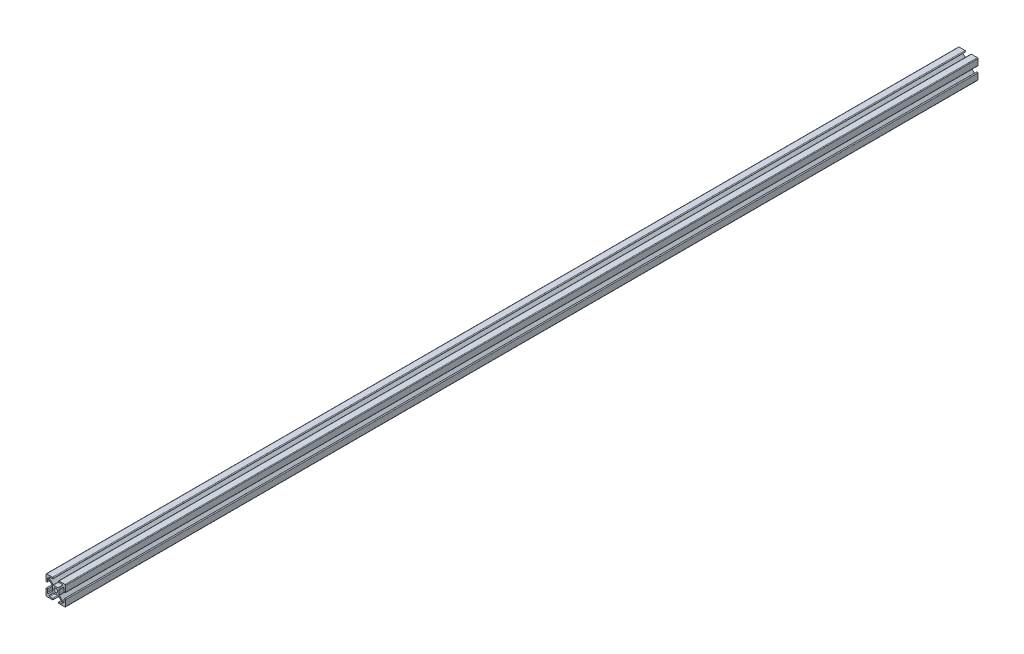
SolidWorks part; units mm, degrees
ref_plane "Alzado" through (0, 0, 0) normal (0, 0, 1) x (1, 0, 0)
ref_plane "Planta" through (0, 0, 0) normal (0, 1, 0) x (1, 0, 0)
ref_plane "Vista lateral" through (0, 0, 0) normal (1, 0, 0) x (0, 0, -1)
sketch "Croquis1" plane through (0, 0, 0) normal (0, 0, 1) x (1, 0, 0)
  line L1 (-14, 15) -> (14, 15)
  line L2 (-15, 14) -> (-15, -14)
  line L3 (-14, -15) -> (14, -15)
  line L4 (15, 14) -> (15, -14)
  line L5 (-15, 15) -> (15, -15) construction
  line L6 (-15, -15) -> (15, 15) construction
  arc A0 (-14, 15) -> (-15, 14) centre (-14, 14) ccw
  arc A1 (14, -15) -> (15, -14) centre (14, -14) ccw
  arc A2 (-14, -15) -> (-15, -14) centre (-14, -14) cw
  arc A3 (15, 14) -> (14, 15) centre (14, 14) ccw
  point P0 (0, 0)
  dimension "D3" = 1
  dimension "D4" = 1
  dimension "D1" = 30
  dimension "D2" = 30
extrude "Saliente-Extruir1" add sketch "Croquis1" against normal blind 1400
sketch "Croquis2" plane through (0, 0, 0) normal (0, 0, 1) x (1, 0, 0)
  circle A0 centre (0, 0) radius 3
  dimension "D1" = 6
sketch "Croquis3" plane through (0, 0, 0) normal (0, 0, 1) x (1, 0, 0)
  line L0 (-15, 0) -> (15, 0) construction
  line L1 (4.0787, -5.4929) -> (9.8787, -11.2929)
  line L2 (-11.2929, 9.8787) -> (-5.4929, 4.0787)
  line L3 (-9.8787, 11.2929) -> (-4.0787, 5.4929)
  line L4 (-13, 9.1716) -> (-13, 5)
  line L5 (-15, 14) -> (-15, -14) construction
  line L6 (-5.2, 3.3716) -> (-5.2, -3.3716)
  line L7 (-9.1716, 13) -> (-5, 13)
  line L8 (9.8787, 11.2929) -> (4.0787, 5.4929)
  line L9 (11.2929, 9.8787) -> (5.4929, 4.0787)
  line L10 (-3.3716, 5.2) -> (3.3716, 5.2)
  line L11 (14, 15) -> (-14, 15) construction
  line L12 (13, 9.1716) -> (13, 5)
  line L13 (5.2, 3.3716) -> (5.2, -3.3716)
  line L14 (15, -14) -> (15, 14) construction
  line L15 (-9.1716, -13) -> (-5, -13)
  line L16 (-3.3716, -5.2) -> (3.3716, -5.2)
  line L17 (-14, -15) -> (14, -15) construction
  line L18 (-5.4929, -4.0787) -> (-11.2929, -9.8787)
  line L19 (5.4929, -4.0787) -> (11.2929, -9.8787)
  line L20 (-4.0787, -5.4929) -> (-9.8787, -11.2929)
  line L21 (5, -13) -> (9.1716, -13)
  line L22 (-13, -5) -> (-13, -9.1716)
  line L23 (13, -5) -> (13, -9.1716)
  line L24 (0, 15) -> (0, -5.2) construction
  line L34 (5, 13) -> (9.1716, 13)
  arc A0 (9.8787, 11.2929) -> (9.1716, 13) centre (9.1716, 12) ccw
  arc A1 (-9.8787, 11.2929) -> (-9.1716, 13) centre (-9.1716, 12) cw
  arc A2 (9.8787, 11.2929) -> (9.1716, 13) centre (9.1716, 12) ccw
  arc A3 (13, 9.1716) -> (11.2929, 9.8787) centre (12, 9.1716) ccw
  arc A4 (11.2929, -9.8787) -> (13, -9.1716) centre (12, -9.1716) ccw
  arc A5 (9.1716, -13) -> (9.8787, -11.2929) centre (9.1716, -12) ccw
  arc A6 (-9.1716, -13) -> (-9.8787, -11.2929) centre (-9.1716, -12) cw
  arc A7 (-11.2929, -9.8787) -> (-13, -9.1716) centre (-12, -9.1716) cw
  arc A8 (-13, 9.1716) -> (-11.2929, 9.8787) centre (-12, 9.1716) cw
  arc A9 (-4.0787, -5.4929) -> (-3.3716, -5.2) centre (-3.3716, -6.2) cw
  arc A10 (3.3716, -5.2) -> (4.0787, -5.4929) centre (3.3716, -6.2) cw
  arc A11 (5.4929, -4.0787) -> (5.2, -3.3716) centre (6.2, -3.3716) cw
  arc A12 (5.2, 3.3716) -> (5.4929, 4.0787) centre (6.2, 3.3716) cw
  arc A13 (3.3716, 5.2) -> (4.0787, 5.4929) centre (3.3716, 6.2) ccw
  arc A14 (-3.3716, 5.2) -> (-4.0787, 5.4929) centre (-3.3716, 6.2) cw
  arc A15 (-5.4929, -4.0787) -> (-5.2, -3.3716) centre (-6.2, -3.3716) ccw
  arc A16 (-5.2, 3.3716) -> (-5.4929, 4.0787) centre (-6.2, 3.3716) ccw
  circle A17 centre (-14, -5) radius 1
  circle A18 centre (-14, 5) radius 1
  circle A19 centre (-5, -14) radius 1
  circle A20 centre (5, -14) radius 1
  circle A21 centre (14, 5) radius 1
  circle A22 centre (14, -5) radius 1
  circle A23 centre (-5, 14) radius 1
  circle A24 centre (5, 14) radius 1
  point P20 (-11.5858, -13)
  point P30 (-13, -11.5858)
  point P43 (-3.7858, -5.2)
  point P50 (3.7858, -5.2)
  point P53 (5.2, -3.7858)
  point P62 (-5.2, -3.7858)
  line M2 (-15, 14) -> (-15, -14)
  line M4 (-14, -15) -> (14, -15)
  line M6 (15, -14) -> (15, 14)
  line M8 (14, 15) -> (-14, 15)
  dimension "D6" = 9.8
  dimension "D7" = 2
  dimension "D12" = 2
  dimension "D19" = 1
  dimension "D2" = 1
  dimension "D3" = 1
  dimension "D4" = 1
  dimension "D16" = 1
  dimension "D5" = 2
  dimension "D8" = 9.8
  dimension "D9" = 2
  dimension "D10" = 9.8
  dimension "D11" = 9.8
  dimension "D15" = 1
  dimension "D20" = 1
  dimension "D23" = 1
  dimension "D24" = 1
  dimension "D27" = 1
  dimension "D28" = 1
extrude "Cortar-Extruir1" cut sketch "Croquis2" against normal through all
extrude "Cortar-Extruir3" cut sketch "Croquis3" against normal through all contours A18 A17 L22 A7 L18 A15 L6 A16 L2 A8 L4 M2 | A24 A23 L7 A1 L3 A14 L10 A13 L8 A0 L34 M8 | A20 L21 A5 L1 A10 L16 A9 L20 A6 L15 A19 M4 | A22 A21 L12 A3 L9 A12 L13 A11 L19 A4 L23 M6
